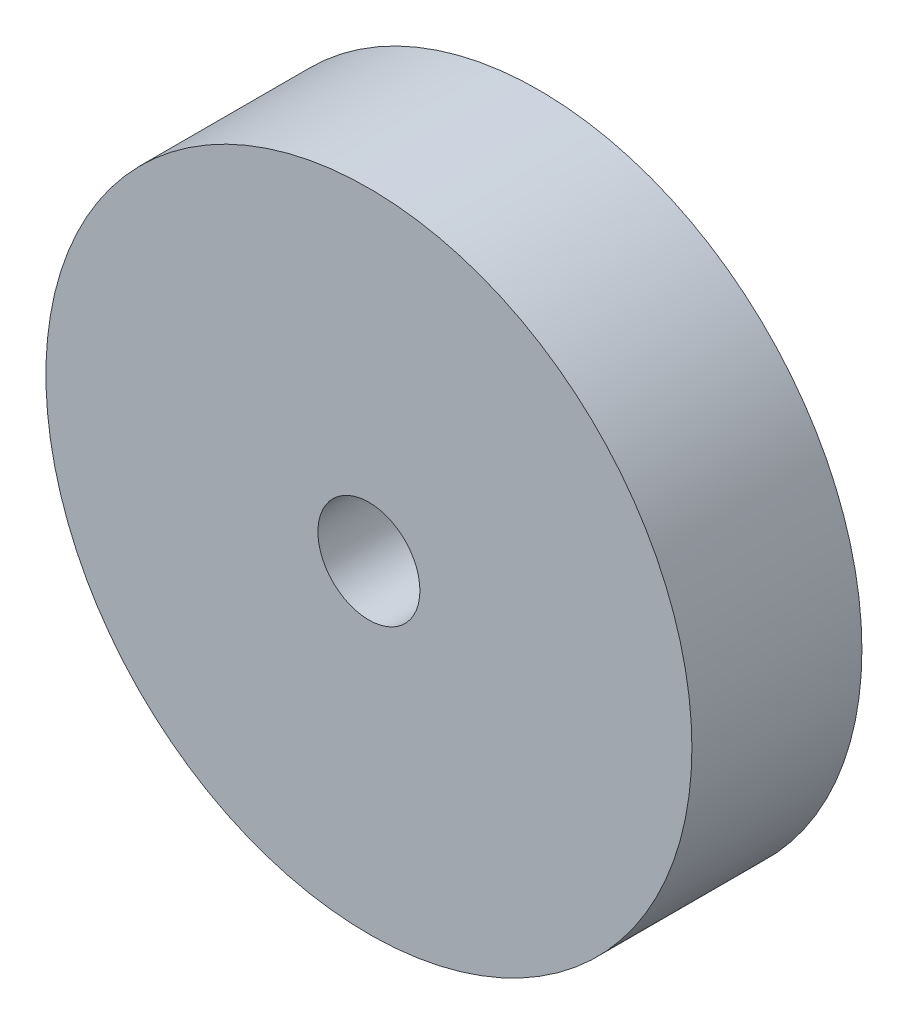
SolidWorks part; units mm, degrees
ref_plane "前视基准面" through (0, 0, 0) normal (0, 0, 1) x (1, 0, 0)
ref_plane "上视基准面" through (0, 0, 0) normal (0, 1, 0) x (1, 0, 0)
ref_plane "右视基准面" through (0, 0, 0) normal (1, 0, 0) x (0, 0, -1)
other "Configuration Table"
sketch "草图1" plane through (0, 0, 0) normal (0, 0, 1) x (1, 0, 0)
  circle A0 centre (0, 0) radius 19
  dimension "D1" = 38
extrude "凸台-拉伸1" add sketch "草图1" along normal blind 10
sketch "草图2" plane through (0, 0, 10) normal (0, 0, 1) x (1, 0, 0)
  circle A0 centre (0, 0) radius 3
  dimension "D1" = 6
extrude "切除-拉伸1" cut sketch "草图2" against normal blind 10
